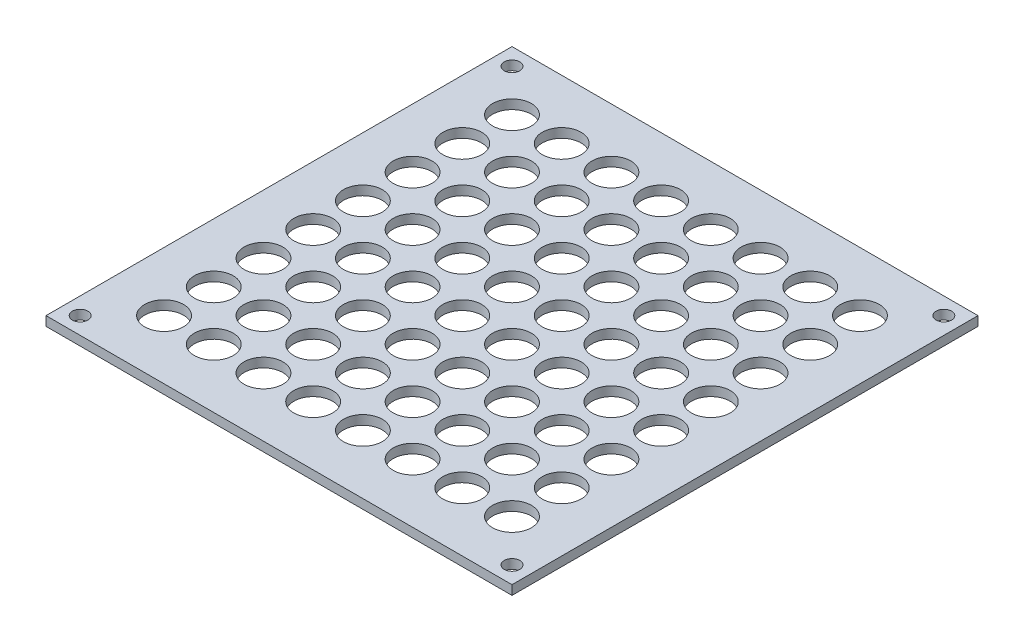
SolidWorks part; units mm, degrees
material "Mogno"
ref_plane "Plano frontal" through (0, 0, 0) normal (0, 0, 1) x (1, 0, 0)
ref_plane "Plano superior" through (0, 0, 0) normal (0, 1, 0) x (1, 0, 0)
ref_plane "Plano direito" through (0, 0, 0) normal (1, 0, 0) x (0, 0, -1)
sketch "Esboço1" plane through (0, 0, 0) normal (0, 1, 0) x (1, 0, 0)
  line L1 (-150, 150) -> (150, 150)
  line L2 (-150, 150) -> (-150, -150)
  line L3 (-150, -150) -> (150, -150)
  line L4 (150, 150) -> (150, -150)
  line L5 (-150, 150) -> (150, -150) construction
  line L6 (-150, -150) -> (150, 150) construction
  point P0 (0, 0)
  dimension "D1" = 300
extrude "Ressalto-extrusão1" add sketch "Esboço1" along normal blind 6
sketch "Esboço2" plane through (0, 6, 0) normal (0, 1, 0) x (1, 0, 0)
  line L0 (-150, 150) -> (-150, -150) construction
  line L1 (-139, 139) -> (139, 139) construction
  line L2 (-139, 139) -> (-139, -139) construction
  line L3 (-139, -139) -> (139, -139) construction
  line L4 (139, 139) -> (139, -139) construction
  line L5 (-139, 139) -> (139, -139) construction
  line L6 (-139, -139) -> (139, 139) construction
  circle A0 centre (-139, 139) radius 5
  circle A1 centre (139, 139) radius 5
  circle A2 centre (139, -139) radius 5
  circle A3 centre (-139, -139) radius 5
  point P0 (0, 0)
  dimension "D2" = 10
  dimension "D1" = 11
extrude "Corte-extrusão1" cut sketch "Esboço2" against normal through all
sketch "Esboço3" plane through (0, 6, 0) normal (0, 1, 0) x (1, 0, 0)
  line L0 (-32, 128) -> (-32, -128) construction
  line L1 (-128, 128) -> (128, 128) construction
  line L2 (-128, 128) -> (-128, -128) construction
  line L3 (-128, -128) -> (128, -128) construction
  line L4 (128, 128) -> (128, -128) construction
  line L5 (-128, 128) -> (128, -128) construction
  line L6 (-128, -128) -> (128, 128) construction
  line L7 (-64, 128) -> (-64, -128) construction
  line L8 (0, 128) -> (0, -128) construction
  line L9 (-96, 128) -> (-96, -128) construction
  line L10 (32, 128) -> (32, -128) construction
  line L11 (64, 128) -> (64, -128) construction
  line L12 (96, 128) -> (96, -128) construction
  line L13 (-128, 96) -> (128, 96) construction
  line L14 (-128, 64) -> (128, 64) construction
  line L15 (-128, 32) -> (128, 32) construction
  line L16 (-128, 0) -> (128, 0) construction
  line L17 (-128, -32) -> (128, -32) construction
  line L18 (-128, -64) -> (128, -64) construction
  line L19 (-128, -96) -> (128, -96) construction
  circle A0 centre (-112, -112) radius 12.5
  circle A1 centre (-80, -112) radius 12.5
  circle A2 centre (-48, -112) radius 12.5
  circle A3 centre (-16, -112) radius 12.5
  circle A4 centre (16, -112) radius 12.5
  circle A5 centre (48, -112) radius 12.5
  circle A6 centre (80, -112) radius 12.5
  circle A7 centre (112, -112) radius 12.5
  circle A8 centre (112, -80) radius 12.5
  circle A9 centre (80, -80) radius 12.5
  circle A10 centre (48, -80) radius 12.5
  circle A11 centre (16, -80) radius 12.5
  circle A12 centre (-16, -80) radius 12.5
  circle A13 centre (-48, -80) radius 12.5
  circle A14 centre (-80, -80) radius 12.5
  circle A15 centre (-112, -80) radius 12.5
  circle A16 centre (112, -16) radius 12.5
  circle A17 centre (112, -48) radius 12.5
  circle A18 centre (80, -16) radius 12.5
  circle A19 centre (80, -48) radius 12.5
  circle A20 centre (48, -16) radius 12.5
  circle A21 centre (48, -48) radius 12.5
  circle A22 centre (16, -16) radius 12.5
  circle A23 centre (16, -48) radius 12.5
  circle A24 centre (-16, -16) radius 12.5
  circle A25 centre (-16, -48) radius 12.5
  circle A26 centre (-48, -16) radius 12.5
  circle A27 centre (-48, -48) radius 12.5
  circle A28 centre (-80, -16) radius 12.5
  circle A29 centre (-80, -48) radius 12.5
  circle A30 centre (-112, -48) radius 12.5
  circle A31 centre (-112, -16) radius 12.5
  circle A32 centre (-112, 16) radius 12.5
  circle A33 centre (-80, 16) radius 12.5
  circle A34 centre (-48, 16) radius 12.5
  circle A35 centre (-16, 16) radius 12.5
  circle A36 centre (16, 16) radius 12.5
  circle A37 centre (48, 16) radius 12.5
  circle A38 centre (80, 16) radius 12.5
  circle A39 centre (112, 16) radius 12.5
  circle A40 centre (112, 48) radius 12.5
  circle A41 centre (80, 48) radius 12.5
  circle A42 centre (48, 48) radius 12.5
  circle A43 centre (16, 48) radius 12.5
  circle A44 centre (-16, 48) radius 12.5
  circle A45 centre (-48, 48) radius 12.5
  circle A46 centre (-80, 48) radius 12.5
  circle A47 centre (-112, 48) radius 12.5
  circle A48 centre (-112, 80) radius 12.5
  circle A49 centre (-80, 80) radius 12.5
  circle A50 centre (-48, 80) radius 12.5
  circle A51 centre (-16, 80) radius 12.5
  circle A52 centre (16, 80) radius 12.5
  circle A53 centre (48, 80) radius 12.5
  circle A54 centre (80, 80) radius 12.5
  circle A55 centre (112, 80) radius 12.5
  circle A56 centre (112, 112) radius 12.5
  circle A57 centre (80, 112) radius 12.5
  circle A58 centre (48, 112) radius 12.5
  circle A59 centre (16, 112) radius 12.5
  circle A60 centre (-16, 112) radius 12.5
  circle A61 centre (-48, 112) radius 12.5
  circle A62 centre (-80, 112) radius 12.5
  circle A63 centre (-112, 112) radius 12.5
  point P0 (0, 0)
  dimension "D4" = 25
  dimension "D1" = 256
  dimension "D2" = 32
  dimension "D3" = 32
  dimension "D5" = 16
  dimension "D6" = 16
extrude "Corte-extrusão2" cut sketch "Esboço3" against normal through all
